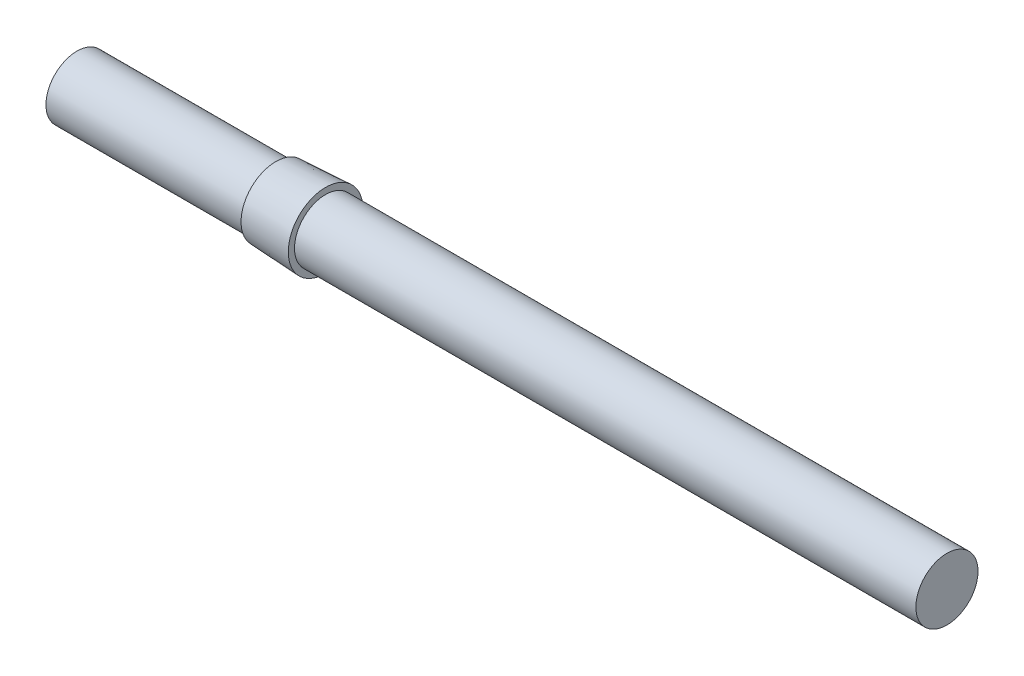
SolidWorks part; units mm, degrees
ref_plane "Front Plane" through (0, 0, 0) normal (1, 0, 0) x (0, 1, 0)
ref_plane "Top Plane" through (0, 0, 0) normal (0, 0, 1) x (0, 1, 0)
ref_plane "Right Plane" through (0, 0, 0) normal (0, 1, 0) x (-1, 0, 0)
sketch "Sketch1" plane through (0, 0, 0) normal (1, 0, 0) x (0, 1, 0)
  circle A0 centre (0, 0) radius 12.5
extrude "Boss-Extrude1" add sketch "Sketch1" along normal blind 350
ref_plane "Plane1" through (80, 0, 0) normal (1, 0, 0) x (0, 1, 0)
ref_plane "Plane2" through (100, 0, 0) normal (1, 0, 0) x (0, 1, 0)
sketch "Sketch2" plane through (80, 0, 0) normal (1, 0, 0) x (0, 1, 0)
  circle A0 centre (0, 0) radius 14
sketch "Sketch3" plane through (100, 0, 0) normal (1, 0, 0) x (0, 1, 0)
  circle A0 centre (0, 0) radius 15
loft "Loft1" add profiles "Sketch3", "Sketch2"
ref_plane "Plane3" through (0, 0, 10) normal (0, 0, 1) x (0, 1, 0)
sketch "Sketch4" plane through (0, 0, 10) normal (0, 0, 1) x (0, 1, 0)
  line L0 (12.5155, -100) -> (-12.5, -100)
  line L1 (-16.5001, -100) -> (16.5001, -100) construction
  line L2 (-12.5, -100) -> (-12.5, -350) construction
  line L5 (4.0078, -100) -> (4.0078, -137)
  line L6 (4.0078, -137) -> (-3.9922, -137)
  line L7 (-3.9922, -137) -> (-3.9922, -100)
extrude "Cut-Extrude2" cut sketch "Sketch4" against normal blind 7 contours L7 L6 L5 L0
